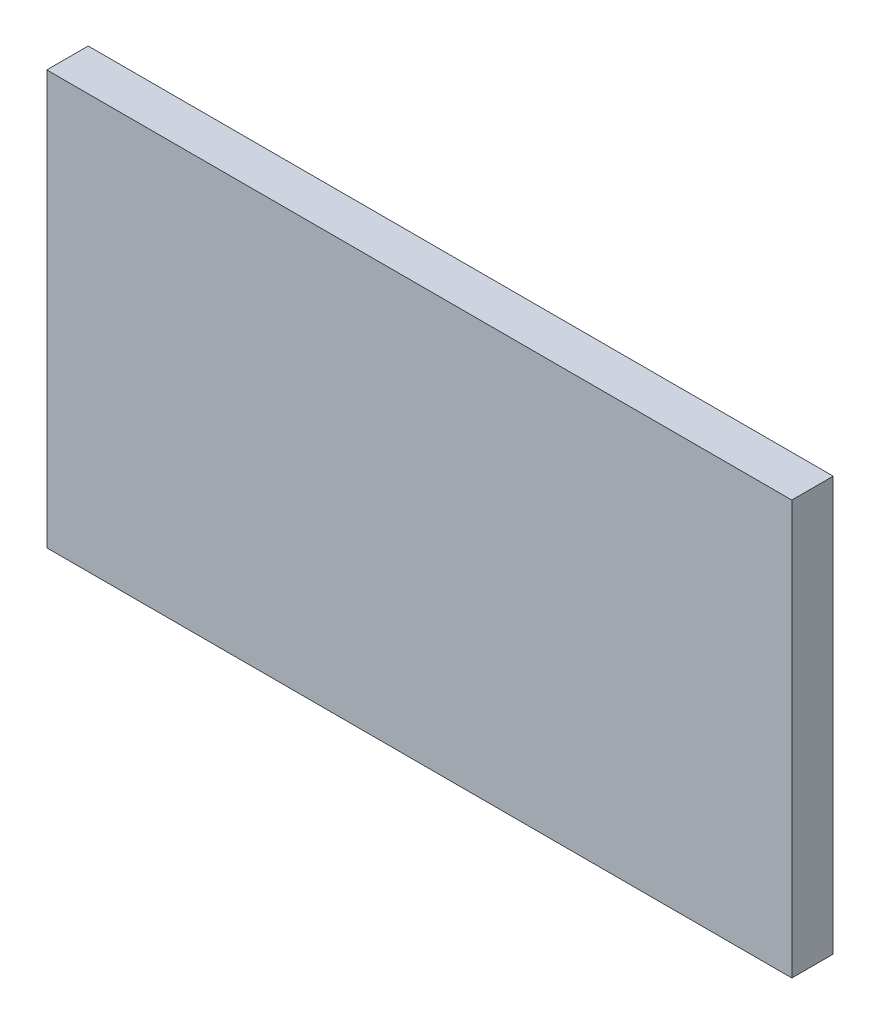
SolidWorks part; units mm, degrees
ref_plane "Front Plane" through (0, 0, 0) normal (0, 0, 1) x (1, 0, 0)
ref_plane "Top Plane" through (0, 0, 0) normal (0, 1, 0) x (1, 0, 0)
ref_plane "Right Plane" through (0, 0, 0) normal (1, 0, 0) x (0, 0, -1)
sketch "Sketch1" plane through (0, 0, 0) normal (0, 0, 1) x (1, 0, 0)
  line L1 (-57.15, 31.75) -> (57.15, 31.75)
  line L2 (-57.15, 31.75) -> (-57.15, -31.75)
  line L3 (-57.15, -31.75) -> (57.15, -31.75)
  line L4 (57.15, 31.75) -> (57.15, -31.75)
  line L5 (-57.15, 31.75) -> (57.15, -31.75) construction
  line L6 (-57.15, -31.75) -> (57.15, 31.75) construction
  point P0 (0, 0)
  dimension "D1" = 114.3
  dimension "D2" = 63.5
extrude "Boss-Extrude1" add sketch "Sketch1" along normal blind 6.35
